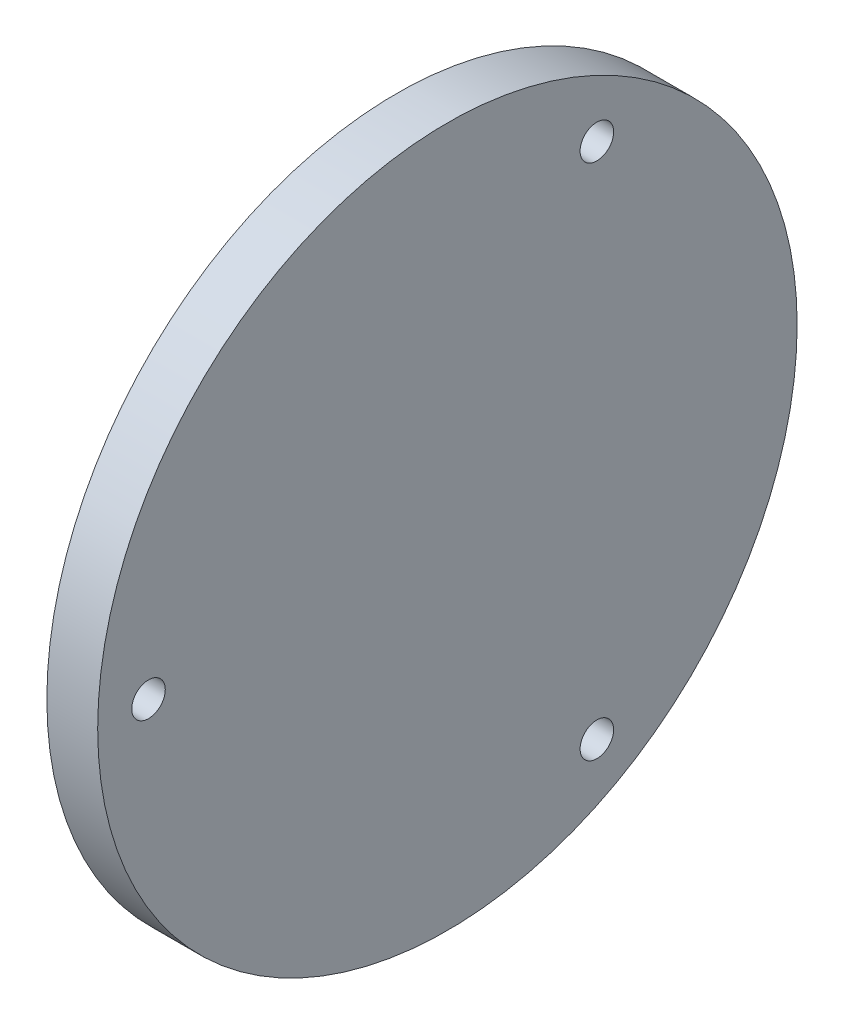
SolidWorks part; units mm, degrees
ref_plane "Front Plane" through (0, 0, 0) normal (0, 0, 1) x (1, 0, 0)
ref_plane "Top Plane" through (0, 0, 0) normal (0, 1, 0) x (1, 0, 0)
ref_plane "Right Plane" through (0, 0, 0) normal (1, 0, 0) x (0, 0, -1)
sketch "Axial profile (mm)" plane through (0, 0, 0) normal (0, 0, 1) x (1, 0, 0)
  line L0 (-110, 0) -> (75, 0) construction
  line L1 (163.7, 0) -> (168.7, 0)
  line L2 (168.7, 0) -> (168.7, 34.4)
  line L3 (168.7, 34.4) -> (163.7, 34.4)
  line L4 (163.7, 34.4) -> (163.7, 0)
revolve "Full revolution" add sketch "Axial profile (mm)" angle 360 about L0
sketch "Sketch2" plane through (0, 0, 0) normal (1, 0, 0) x (0, 0, -1)
  circle A0 centre (-29.4, 0) radius 1.65
  circle A1 centre (14.7, -25.4611) radius 1.65
  circle A2 centre (14.7, 25.4611) radius 1.65
extrude "Axial holes" cut sketch "Sketch2" against normal through all and the other way through all
sketch "Sketch3" plane through (0, 0, 0) normal (1, 0, 0) x (0, 0, -1)
  circle A0 centre (29.4, 0) radius 1.65
  circle A1 centre (-14.7, 25.4611) radius 1.65
  circle A2 centre (-14.7, -25.4611) radius 1.65
extrude "Cut-Extrude2" cut sketch "Sketch3" against normal blind 3.5 from offset 165.2
